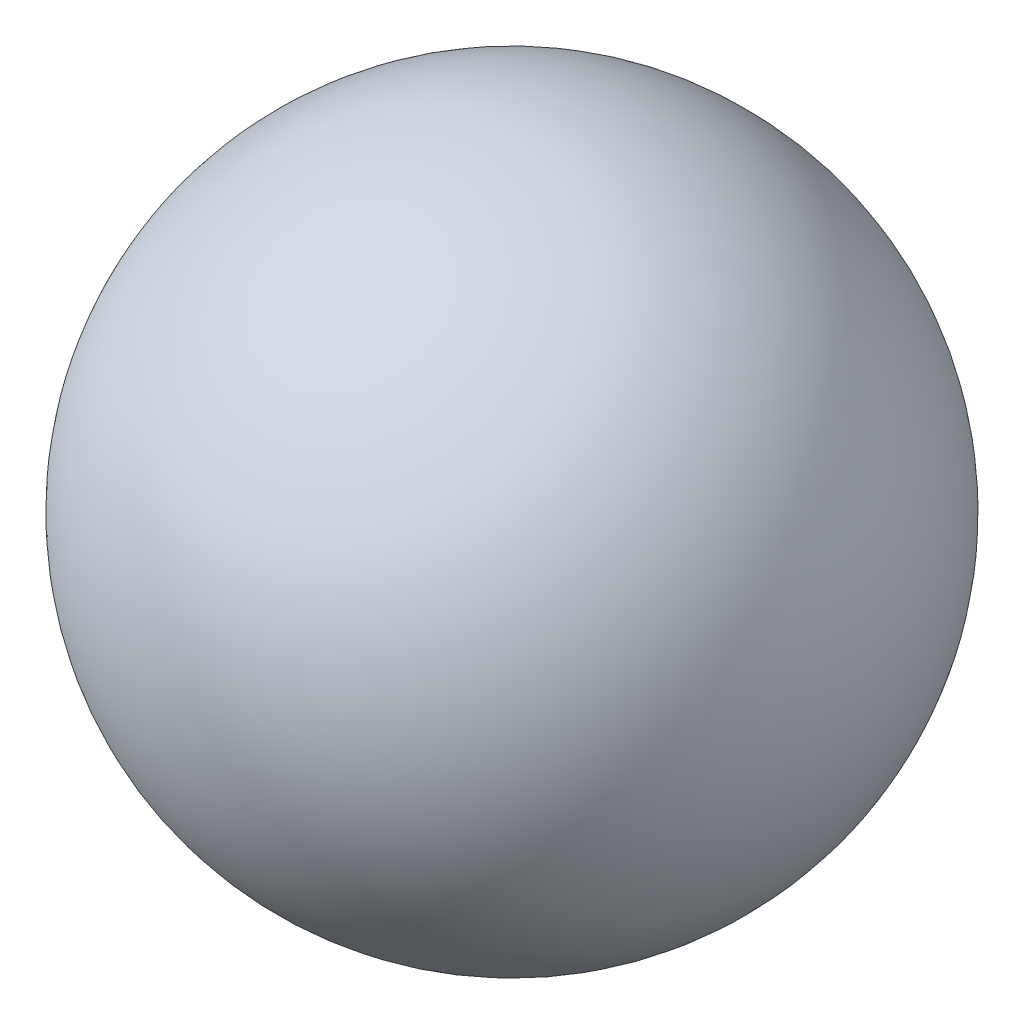
SolidWorks part; units mm, degrees
ref_plane "Front Plane" through (0, 0, 0) normal (0, 0, 1) x (1, 0, 0)
ref_plane "Top Plane" through (0, 0, 0) normal (0, 1, 0) x (1, 0, 0)
ref_plane "Right Plane" through (0, 0, 0) normal (1, 0, 0) x (0, 0, -1)
sketch "Sketch1" plane through (0, 0, 0) normal (0, 0, 1) x (1, 0, 0)
  line L0 (-8, 0) -> (8, 0)
  arc A0 (8, 0) -> (-8, 0) centre (0, 0) cw
  dimension "D1" = 16
revolve "Revolve1" add sketch "Sketch1" angle 360 about L0
scale "Scale1" scale about centroid uniform scaling yes scale factor 0.1
